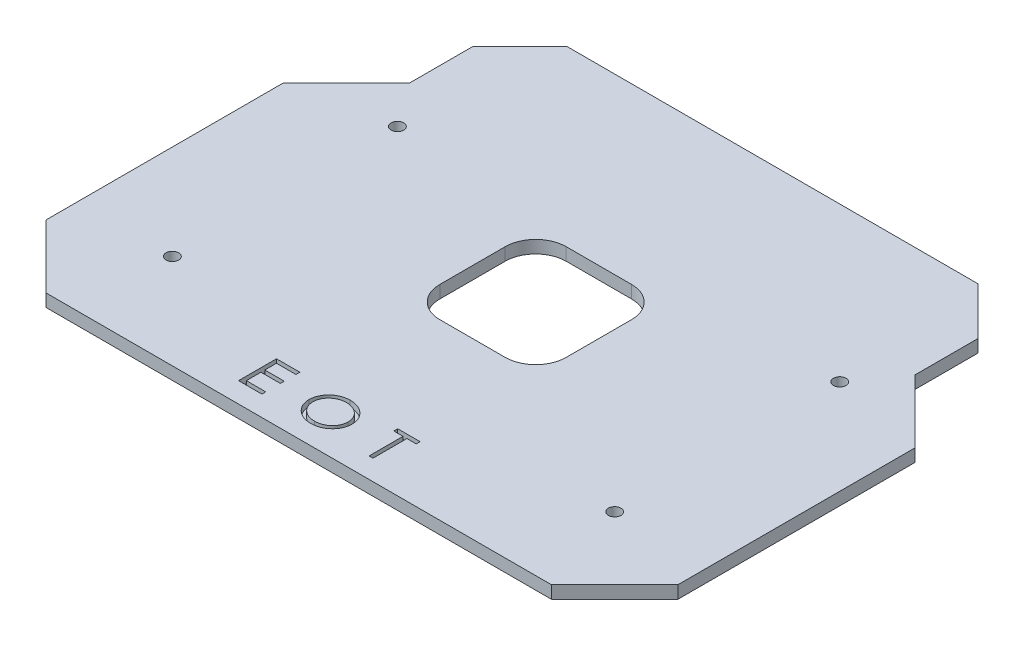
SolidWorks part; units mm, degrees
ref_plane "Front Plane" through (0, 0, 0) normal (0, 0, 1) x (1, 0, 0)
ref_plane "Top Plane" through (0, 0, 0) normal (0, 1, 0) x (1, 0, 0)
ref_plane "Right Plane" through (0, 0, 0) normal (1, 0, 0) x (0, 0, -1)
sketch "Sketch1" plane through (0, 0, 0) normal (0, 1, 0) x (1, 0, 0)
  line L0 (-80, 9.4574) -> (-65, 24.4574)
  line L1 (65, 24.4574) -> (25, 24.4574)
  line L3 (65, 24.4574) -> (80, 9.4574)
  line L4 (25, 24.4574) -> (-25, 24.4574)
  line L6 (-80, -10.5426) -> (-80, 9.4574)
  line L9 (-25, 24.4574) -> (-65, 24.4574)
  line L15 (80, -10.5426) -> (80, 9.4574)
  line L17 (80, -125.5426) -> (-80, -125.5426)
  line L19 (100, -105.5426) -> (100, -30.5426)
  line L20 (100, -105.5426) -> (80, -125.5426)
  line L21 (80, -10.5426) -> (100, -30.5426)
  line L22 (-80, -10.5426) -> (-100, -30.5426)
  line L23 (-100, -105.5426) -> (-80, -125.5426)
  line L24 (-100, -105.5426) -> (-100, -30.5426)
  line L25 (0, -125.5426) -> (0, -10.5426) construction
  line L28 (10.3376, -30.5426) -> (-10.3376, -30.5426)
  line L29 (20, -40.205) -> (20, -60.8802)
  line L30 (10.3376, -70.5426) -> (-10.3376, -70.5426)
  line L31 (-20, -40.205) -> (-20, -60.8802)
  line L32 (20, -30.5426) -> (-20, -70.5426) construction
  line L33 (20, -70.5426) -> (-20, -30.5426) construction
  arc A0 (20, -60.8802) -> (10.3376, -70.5426) centre (10.3376, -60.8802) cw
  arc A1 (-20, -60.8802) -> (-10.3376, -70.5426) centre (-10.3376, -60.8802) ccw
  arc A2 (-20, -40.205) -> (-10.3376, -30.5426) centre (-10.3376, -40.205) cw
  arc A3 (20, -40.205) -> (10.3376, -30.5426) centre (10.3376, -40.205) ccw
  circle A4 centre (70, -24.3168) radius 2
  circle A5 centre (-70, -24.3168) radius 2
  circle A6 centre (70, -95.5426) radius 2
  circle A7 centre (-70, -95.5426) radius 2
  point P21 (0, -50.5426)
  point P53 (80, -0.5426)
  point P55 (-80, -0.5426)
  point P59 (50, -70.5426)
  point P66 (-50, -70.5426)
  point P82 (-30, 30)
  point P83 (30, 30)
  point P85 (30, -50)
  point P86 (-30, -50)
  point P94 (-30, 30)
  dimension "D13" = 9.6624
  dimension "D2" = 30
  dimension "D11" = 40
  dimension "D12" = 40
extrude "Boss-Extrude1" add sketch "Sketch1" along normal blind 4
sketch "Sketch2" plane through (0, 4, 0) normal (0, 1, 0) x (1, 0, 0)
  text T0 "E O T" font "Century Gothic" height 12
extrude "Cut-Extrude1" cut sketch "Sketch2" against normal blind 2
